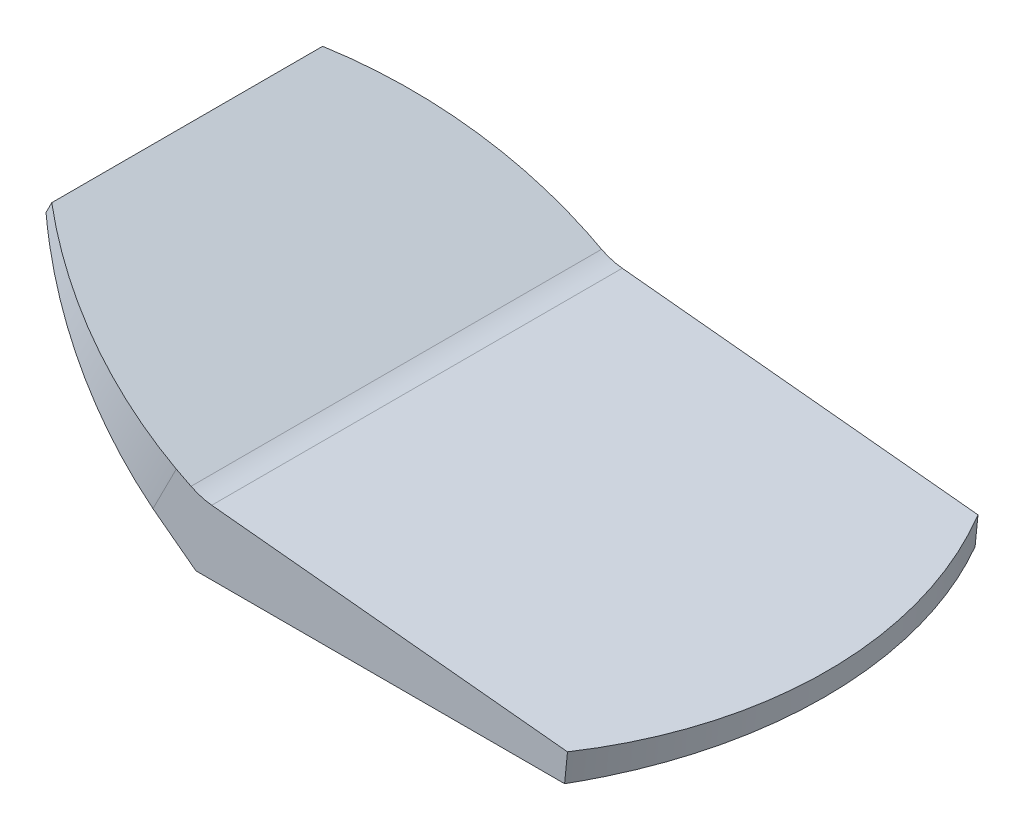
SolidWorks part; units mm, degrees
ref_plane "Front Plane" through (0, 0, 0) normal (0, 0, 1) x (1, 0, 0)
ref_plane "Top Plane" through (0, 0, 0) normal (0, 1, 0) x (1, 0, 0)
ref_plane "Right Plane" through (0, 0, 0) normal (1, 0, 0) x (0, 0, -1)
sketch "Sketch1" plane through (0, 0, 0) normal (0, 0, 1) x (1, 0, 0)
  line L0 (433.5511, 624.0548) -> (524.1181, 578.0747)
  line L1 (533.0823, 575.4497) -> (710.8345, 557.6264)
  line L2 (710.8345, 547.4101) -> (526.2364, 547.4101)
  line L3 (526.2364, 547.4101) -> (431.0532, 619.1347)
  line L4 (710.8345, 557.6264) -> (710.8345, 547.4101)
  line L5 (433.5511, 624.0548) -> (431.0532, 619.1347)
  arc A0 (524.1181, 578.0747) -> (533.0823, 575.4497) centre (535.6165, 600.723) ccw
  dimension "D1" = 25.4
extrude "Extrude1" add sketch "Sketch1" against normal blind 177.8
ref_plane "Plane1" through (62.433, 622.6422, 0) normal (0.0998, 0.995, 0) x (-0.995, 0.0998, 0)
sketch "Sketch5" plane through (62.433, 622.6422, 0) normal (0.0998, 0.995, 0) x (-0.995, 0.0998, 0)
  line L0 (-627.8735, 0) -> (-668.1454, 0)
  line L2 (-473.0095, -177.8) -> (-473.0095, 0) construction
  line L3 (-651.653, 0) -> (-473.0095, 0) construction
  line L4 (-668.1454, 0) -> (-668.1454, -177.8)
  line L5 (-627.8735, -177.8) -> (-668.1454, -177.8)
  arc A0 (-627.8735, 0) -> (-627.8735, -177.8) centre (-473.0095, -88.9) ccw
extrude "Extrude5" cut sketch "Sketch5" against normal blind 44.45
ref_plane "Plane2" through (340.748, 671.1703, 0) normal (0.4527, 0.8917, 0) x (-0.8917, 0.4527, 0)
sketch "Sketch7" plane through (340.748, 671.1703, 0) normal (0.4527, 0.8917, 0) x (-0.8917, 0.4527, 0)
  line L3 (-205.6487, 0) -> (-76.4739, 0)
  line L4 (-76.4739, 0) -> (-76.4739, -177.8)
  line L5 (-76.4739, -177.8) -> (-205.6487, -177.8)
  line L6 (-101.3226, -145.636) -> (-101.3226, -32.164)
  arc A0 (-205.6487, 0) -> (-101.3226, -32.164) centre (-202.0597, -173.6353) cw
  arc A1 (-205.6487, -177.8) -> (-101.3226, -145.636) centre (-202.0597, -4.1647) ccw
extrude "Extrude6" cut sketch "Sketch7" against normal blind 44.45 contours A1 L5 L4 L3 A0 L6
ref_plane "Plane3" through (0, 0, 6.35) normal (0, 0, 1) x (1, 0, 0)
sketch "Sketch8" plane through (0, 0, 6.35) normal (0, 0, 1) x (1, 0, 0)
  line L2 (429.0333, 623.4106) -> (519.2517, 568.7736)
  line L3 (524.8542, 566.9744) -> (714.1884, 552.3766)
  arc A0 (519.2517, 568.7736) -> (524.8542, 566.9744) centre (525.8305, 579.6368) ccw
  dimension "D1" = 12.7
